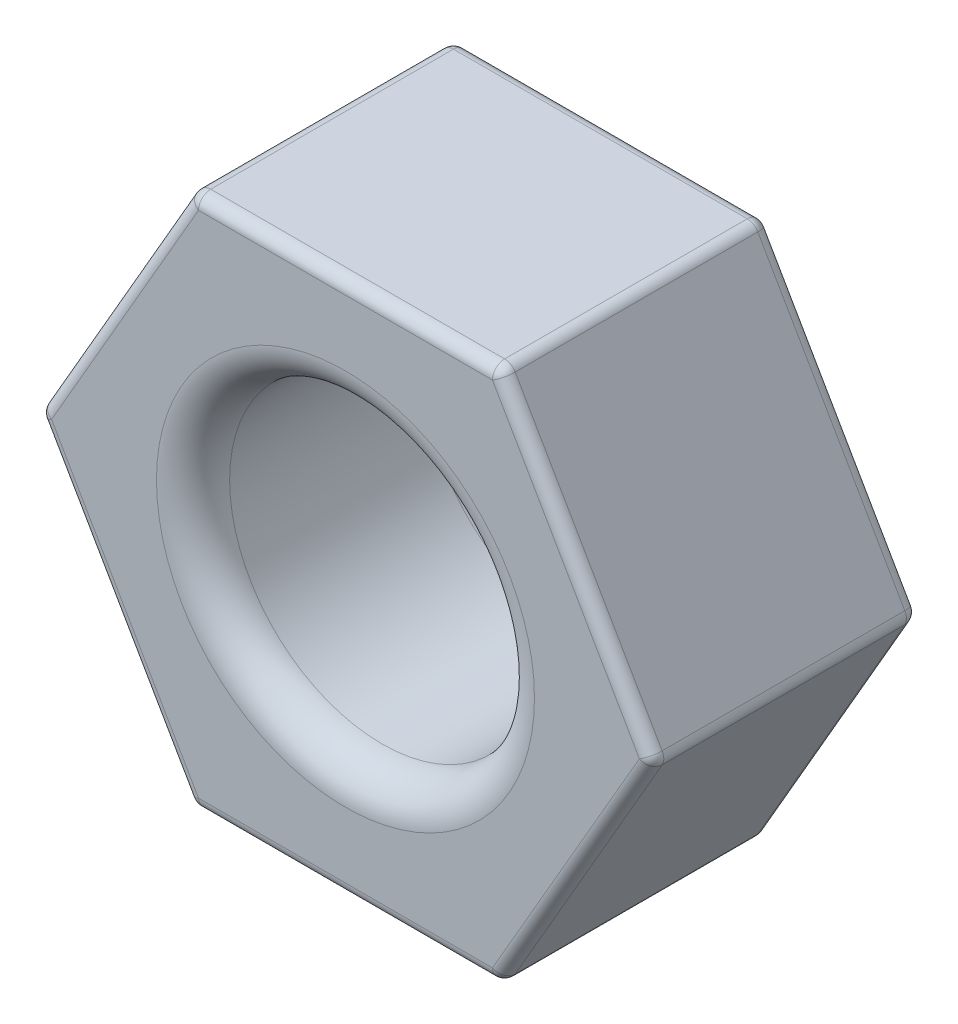
SolidWorks part; units mm, degrees
material "Alloy Steel"
ref_plane "Front Plane" through (0, 0, 0) normal (0, 0, 1) x (1, 0, 0)
ref_plane "Top Plane" through (0, 0, 0) normal (0, 1, 0) x (1, 0, 0)
ref_plane "Right Plane" through (0, 0, 0) normal (1, 0, 0) x (0, 0, -1)
sketch "Sketch1" plane through (0, 0, 0) normal (0, 0, 1) x (1, 0, 0)
  line L0 (3.175, 0) -> (6.4158, 0) construction
  line L1 (1.5875, -2.7496) -> (3.2079, -5.5563) construction
  line L2 (3.2079, -5.5563) -> (6.4158, 0)
  line L3 (-3.2079, -5.5562) -> (3.2079, -5.5563)
  line L4 (-6.4158, 0) -> (-3.2079, -5.5562)
  line L5 (-3.2079, 5.5563) -> (-6.4158, 0)
  line L6 (3.2079, 5.5562) -> (-3.2079, 5.5563)
  line L7 (6.4158, 0) -> (3.2079, 5.5562)
  circle A0 centre (0, 0) radius 3.175
  point P19 (0, 0)
  dimension "D1" = 6.35
  dimension "D2" = 60
  dimension "D3" = 5.5562
  dimension "D4" = 6
extrude "Boss-Extrude1" add sketch "Sketch1" along normal blind 5.5626
fillet "Fillet1" radius 0.254 18 edges at (-4.8119, -2.7781, 0) (0, -5.5563, 0) (4.8119, -2.7781, 0) (4.8119, 2.7781, 0) (0, 5.5563, 0) (-4.8119, 2.7781, 0) (-6.4158, 0, 2.7813) (-3.2079, -5.5562, 2.7813) (3.2079, -5.5563, 2.7813) (-3.2079, 5.5563, 2.7813) (3.2079, 5.5562, 2.7813) (6.4158, 0, 2.7813) (4.8119, -2.7781, 5.5626) (0, -5.5563, 5.5626) (-4.8119, -2.7781, 5.5626) (-4.8119, 2.7781, 5.5626) (0, 5.5563, 5.5626) (4.8119, 2.7781, 5.5626)
fillet "Fillet2" radius 0.762 2 edges at (3.175, 0, 5.5626) (3.175, 0, 0)
